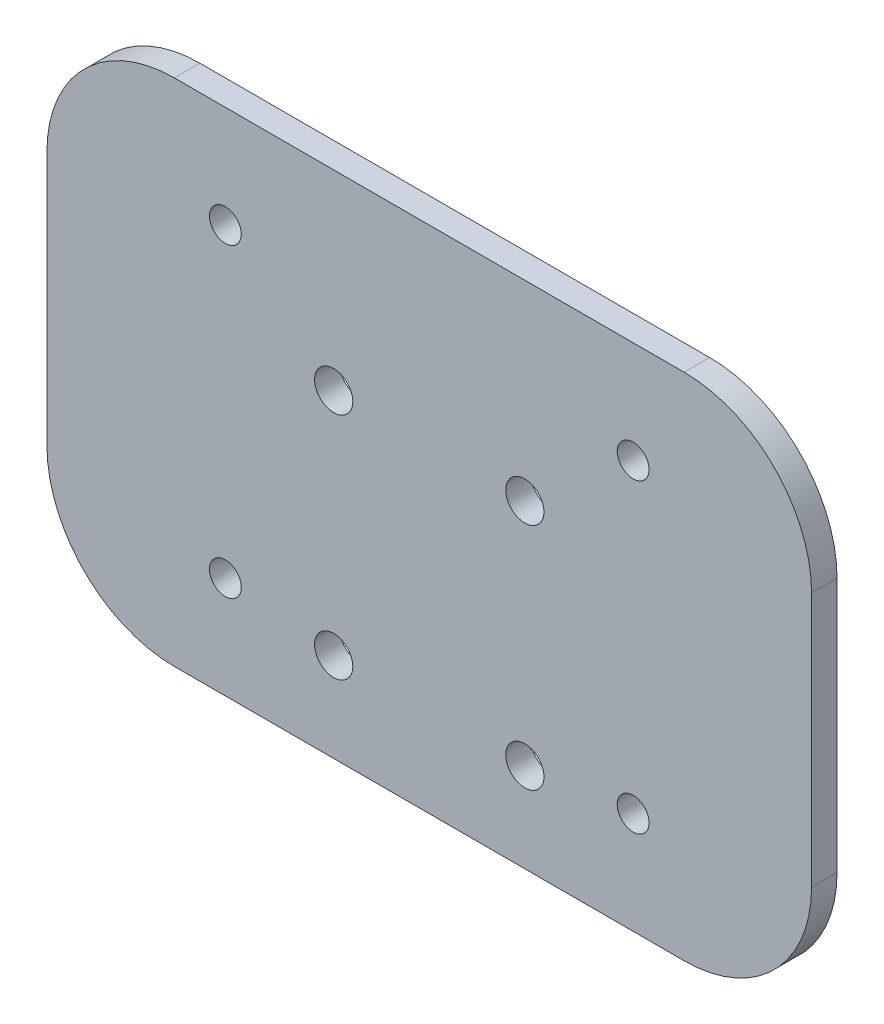
SolidWorks part; units mm, degrees
material "水绿环氧树脂"
ref_plane "前视基准面" through (0, 0, 0) normal (0, 0, 1) x (1, 0, 0)
ref_plane "上视基准面" through (0, 0, 0) normal (0, 1, 0) x (1, 0, 0)
ref_plane "右视基准面" through (0, 0, 0) normal (1, 0, 0) x (0, 0, -1)
sketch "草图1" plane through (0, 0, 0) normal (0, 0, 1) x (1, 0, 0)
  line L1 (-16, -12) -> (16, -12) construction
  line L2 (-16, -12) -> (-16, 12) construction
  line L3 (-16, 12) -> (16, 12) construction
  line L4 (16, -12) -> (16, 12) construction
  line L5 (-16, -12) -> (16, 12) construction
  line L6 (-16, 12) -> (16, -12) construction
  line L7 (-30, -20) -> (30, -20)
  line L8 (-30, -20) -> (-30, 20)
  line L9 (-30, 20) -> (30, 20)
  line L10 (30, -20) -> (30, 20)
  line L11 (-30, -20) -> (30, 20) construction
  line L12 (-30, 20) -> (30, -20) construction
  circle A0 centre (-16, 12) radius 1.25
  circle A1 centre (16, 12) radius 1.25
  circle A2 centre (16, -12) radius 1.25
  circle A3 centre (-16, -12) radius 1.25
  point P0 (0, 0)
  point P10 (0, 0)
  dimension "D3" = 2.5
  dimension "D4" = 2.5
  dimension "D5" = 2.5
  dimension "D6" = 2.5
  dimension "D1" = 24
  dimension "D2" = 32
  dimension "D7" = 40
  dimension "D8" = 60
extrude "凸台-拉伸1" add sketch "草图1" along normal blind 2
fillet "圆角1" radius 10 4 edges at (-30, 20, 1) (30, 20, 1) (30, -20, 1) (-30, -20, 1)
sketch "草图2" plane through (0, 0, 2) normal (0, 0, 1) x (1, 0, 0)
  line L0 (0, 0) -> (0, -4) construction
  line L2 (-7.5, -13) -> (7.5, -13) construction
  line L3 (-7.5, -13) -> (-7.5, 5) construction
  line L4 (-7.5, 5) -> (7.5, 5) construction
  line L5 (7.5, -13) -> (7.5, 5) construction
  line L6 (-7.5, -13) -> (7.5, 5) construction
  line L7 (-7.5, 5) -> (7.5, -13) construction
  circle A0 centre (-7.5, 5) radius 1.5
  circle A1 centre (7.5, 5) radius 1.5
  circle A2 centre (7.5, -13) radius 1.5
  circle A3 centre (-7.5, -13) radius 1.5
  dimension "D4" = 3
  dimension "D5" = 3
  dimension "D6" = 3
  dimension "D7" = 3
  dimension "D1" = 4
  dimension "D2" = 18
  dimension "D3" = 15
extrude "切除-拉伸1" cut sketch "草图2" against normal blind 2
